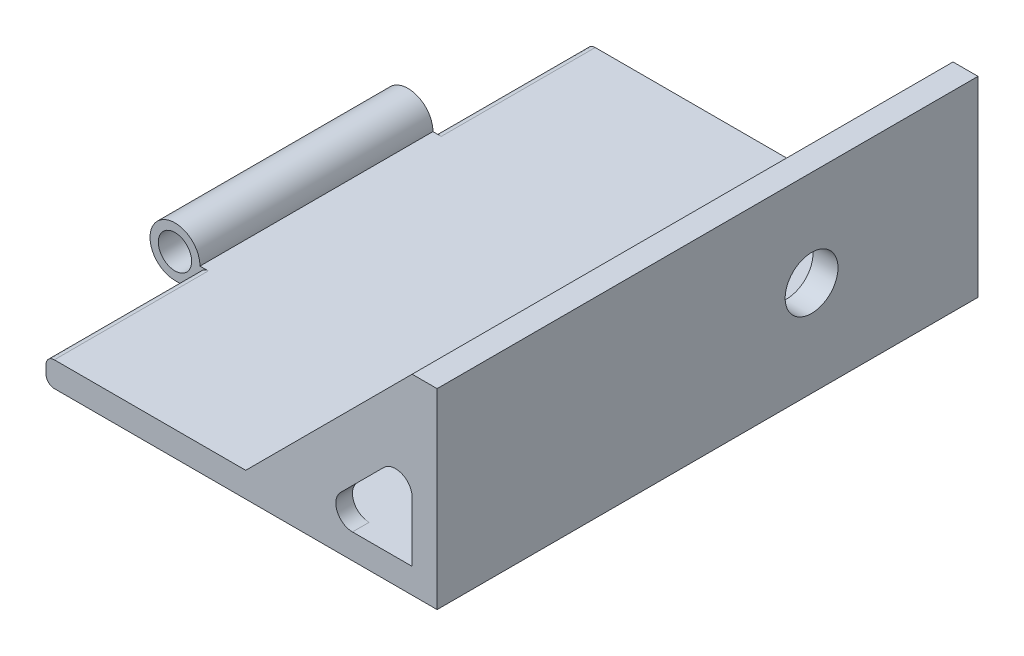
SolidWorks part; units mm, degrees
ref_plane "Front Plane" through (0, 0, 0) normal (0, 0, 1) x (1, 0, 0)
ref_plane "Top Plane" through (0, 0, 0) normal (0, 1, 0) x (1, 0, 0)
ref_plane "Right Plane" through (0, 0, 0) normal (1, 0, 0) x (0, 0, -1)
sketch "Sketch1" plane through (0, 0, 0) normal (0, 1, 0) x (1, 0, 0)
  line L1 (-25, 32.5) -> (25, 32.5)
  line L2 (-25, 32.5) -> (-25, -32.5)
  line L3 (-25, -32.5) -> (25, -32.5)
  line L4 (25, 32.5) -> (25, -32.5)
  line L5 (-25, 32.5) -> (25, -32.5) construction
  line L6 (-25, -32.5) -> (25, 32.5) construction
  point P0 (0, 0)
  dimension "D1" = 50
  dimension "D2" = 65
extrude "Boss-Extrude1" add sketch "Sketch1" along normal blind 3
sketch "Sketch2" plane through (0, 0, 32.5) normal (0, 0, 1) x (1, 0, 0)
  line L0 (-25, 0) -> (25, 0) construction
  line L1 (-25, 3) -> (-22, 3)
  line L2 (-25, 3) -> (-25, 0)
  line L3 (-25, 0) -> (-22, 0)
  line L4 (-22, 3) -> (-22, 0)
  dimension "D1" = 3
extrude "Cut-Extrude1" cut sketch "Sketch2" against normal blind 18.5
sketch "Sketch3" plane through (0, 0, -32.5) normal (0, 0, -1) x (-1, 0, 0)
  line L0 (-25, 0) -> (25, 0) construction
  line L1 (25, 3) -> (22, 3)
  line L2 (25, 3) -> (25, 0)
  line L3 (25, 0) -> (22, 0)
  line L4 (22, 3) -> (22, 0)
  dimension "D1" = 3
extrude "Cut-Extrude2" cut sketch "Sketch3" against normal blind 18.5
sketch "Sketch4" plane through (0, 0, 14) normal (0, 0, 1) x (1, 0, 0)
  circle A0 centre (-25, 3) radius 3
extrude "Boss-Extrude2" add sketch "Sketch4" against normal blind 28
sketch "Sketch5" plane through (0, 0, 14) normal (0, 0, 1) x (1, 0, 0)
  circle A0 centre (-25, 3) radius 2
  dimension "D1" = 4
extrude "Cut-Extrude3" cut sketch "Sketch5" against normal blind 28
fillet "Fillet1" radius 1 4 edges at (-22, 0, 23.25) (-22, 0, -23.25) (-22, 3, -23.25) (-22, 3, 23.25)
sketch "Sketch6" plane through (0, 3, 0) normal (0, 1, 0) x (1, 0, 0)
  line L0 (-21, -32.5) -> (25, -32.5) construction
  line L1 (25, 32.5) -> (22, 32.5)
  line L2 (25, 32.5) -> (25, -32.5)
  line L3 (25, -32.5) -> (22, -32.5)
  line L4 (22, 32.5) -> (22, -32.5)
  dimension "D1" = 3
extrude "Boss-Extrude3" add sketch "Sketch6" along normal blind 20
sketch "Sketch7" plane through (0, 0, 32.5) normal (0, 0, 1) x (1, 0, 0)
  line L0 (22, 23) -> (22, 3)
  line L1 (22, 3) -> (2, 3)
  line L2 (-21, 3) -> (22, 3) construction
  line L3 (2, 3) -> (22, 23)
  dimension "D1" = 45
extrude "Boss-Extrude4" add sketch "Sketch7" against normal blind 2
sketch "Sketch8" plane through (0, 0, -32.5) normal (0, 0, -1) x (-1, 0, 0)
  line L0 (-22, 23) -> (-2, 3)
  line L1 (-2, 3) -> (-22, 3)
  line L2 (-22, 3) -> (-22, 23)
extrude "Boss-Extrude5" add sketch "Sketch8" against normal blind 2
sketch "Sketch9" plane through (0, 0, 32.5) normal (0, 0, 1) x (1, 0, 0)
  line L0 (22, 15) -> (22, 3)
  line L1 (22, 3) -> (10, 3)
  line L2 (10, 3) -> (22, 15)
  line L3 (22, 23) -> (2, 3) construction
  dimension "D1" = 180
  dimension "D2" = 0
  dimension "D3" = 5.6569
  dimension "D4" = 12
extrude "Cut-Extrude4" cut sketch "Sketch9" against normal blind 82
fillet "Fillet2" radius 2 4 edges at (10, 3, -31.5) (22, 15, -31.5) (10, 3, 31.5) (22, 15, 31.5)
sketch "Sketch10" plane through (25, 0, 0) normal (1, 0, 0) x (0, 0, -1)
  line L0 (-32.5, 23) -> (-32.5, 0) construction
  line L1 (-32.5, 23) -> (32.5, 23) construction
  circle A0 centre (12.5, 11.5) radius 3.175
  dimension "D1" = 6.35
  dimension "D3" = 11.5
  dimension "D2" = 45
extrude "Cut-Extrude5" cut sketch "Sketch10" against normal blind 82
